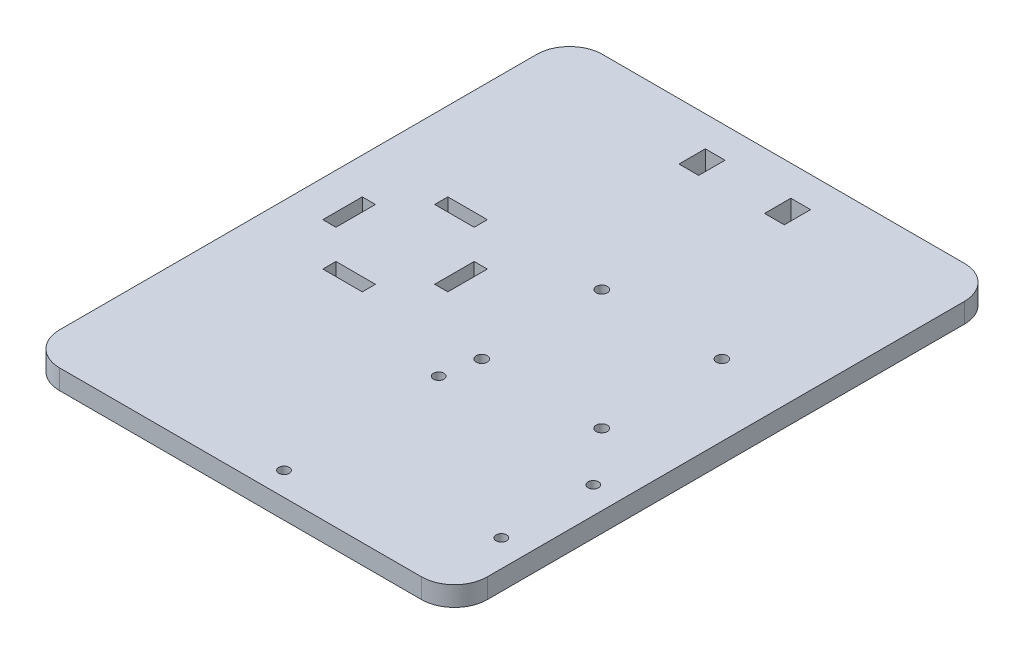
SolidWorks part; units mm, degrees
ref_plane "Front Plane" through (0, 0, 0) normal (0, 0, 1) x (1, 0, 0)
ref_plane "Top Plane" through (0, 0, 0) normal (0, 1, 0) x (1, 0, 0)
ref_plane "Right Plane" through (0, 0, 0) normal (1, 0, 0) x (0, 0, -1)
other "Configuration Table"
sketch "Sketch1" plane through (0, 0, 0) normal (0, 1, 0) x (1, 0, 0)
  line L5 (20, 26.8701) -> (-12.0872, -16.2392) construction
  line L6 (-6.8701, 0) -> (46.8701, 0) construction
  line L19 (-19, 6) -> (-15, 6)
  line L20 (-19, 6) -> (-19, -6)
  line L21 (-19, -6) -> (-15, -6)
  line L22 (-15, 6) -> (-15, -6)
  line L24 (6, 19) -> (-6, 19)
  line L25 (6, 19) -> (6, 15)
  line L26 (6, 15) -> (-6, 15)
  line L27 (-6, 19) -> (-6, 15)
  line L28 (19, -6) -> (19, 6)
  line L29 (19, -6) -> (15, -6)
  line L30 (15, -6) -> (15, 6)
  line L31 (19, 6) -> (15, 6)
  line L32 (-6, -19) -> (6, -19)
  line L33 (-6, -19) -> (-6, -15)
  line L34 (-6, -15) -> (6, -15)
  line L35 (6, -19) -> (6, -15)
  line L39 (20.4791, 70.7636) -> (26.4791, 70.7636)
  line L40 (20.4791, 70.7636) -> (20.4791, 62.7636)
  line L41 (90, 80) -> (-20, 80)
  line L42 (100, 70) -> (100, -75)
  line L43 (90, -85) -> (-20, -85)
  line L44 (-30, 70) -> (-30, -75)
  line L45 (20.4791, 62.7636) -> (26.4791, 62.7636)
  line L46 (26.4791, 70.7636) -> (26.4791, 62.7636)
  line L47 (46.4791, 70.7636) -> (52.4791, 70.7636)
  line L48 (46.4791, 70.7636) -> (46.4791, 62.7636)
  line L49 (46.4791, 62.7636) -> (52.4791, 62.7636)
  line L50 (52.4791, 70.7636) -> (52.4791, 62.7636)
  circle A0 centre (41.8048, 18) radius 1.7
  circle A1 centre (78.3048, 17.9692) radius 1.7
  circle A2 centre (78.3048, -18.5308) radius 1.7
  circle A3 centre (41.8048, -18.5) radius 1.7
  circle A4 centre (39.8065, -29.5939) radius 1.5875
  circle A5 centre (91.8765, -34.6739) radius 1.5875
  circle A6 centre (91.8765, -62.6139) radius 1.5875
  circle A7 centre (41.0765, -77.8539) radius 1.5875
  arc A8 (-30, -75) -> (-20, -85) centre (-20, -75) ccw
  arc A9 (100, -75) -> (90, -85) centre (90, -75) cw
  arc A10 (100, 70) -> (90, 80) centre (90, 70) ccw
  arc A11 (-20, 80) -> (-30, 70) centre (-20, 70) ccw
  point P0 (0, 0)
  point P6 (20, 0)
  point P29 (0, 0)
  point P65 (100, -85)
  point P68 (100, 80)
  point P71 (-30, 80)
  dimension "D14" = 3.4
  dimension "D15" = 3.4
  dimension "D16" = 3.4
  dimension "D17" = 3.4
  dimension "D23" = 10
  dimension "D1" = 38
  dimension "D2" = 38
  dimension "D3" = 4
  dimension "D4" = 12
  dimension "D5" = 4
  dimension "D6" = 80
  dimension "D7" = 100
  dimension "D8" = 19
  dimension "D9" = 6
  dimension "D10" = 20
  dimension "D11" = 16.2392
  dimension "D12" = 130
  dimension "D13" = 165
  dimension "D18" = 36.5
  dimension "D19" = 36.5
  dimension "D20" = 36.5
  dimension "D21" = 36.5
  dimension "D22" = 62
extrude "Boss-Extrude2" add sketch "Sketch1" along normal blind 6
